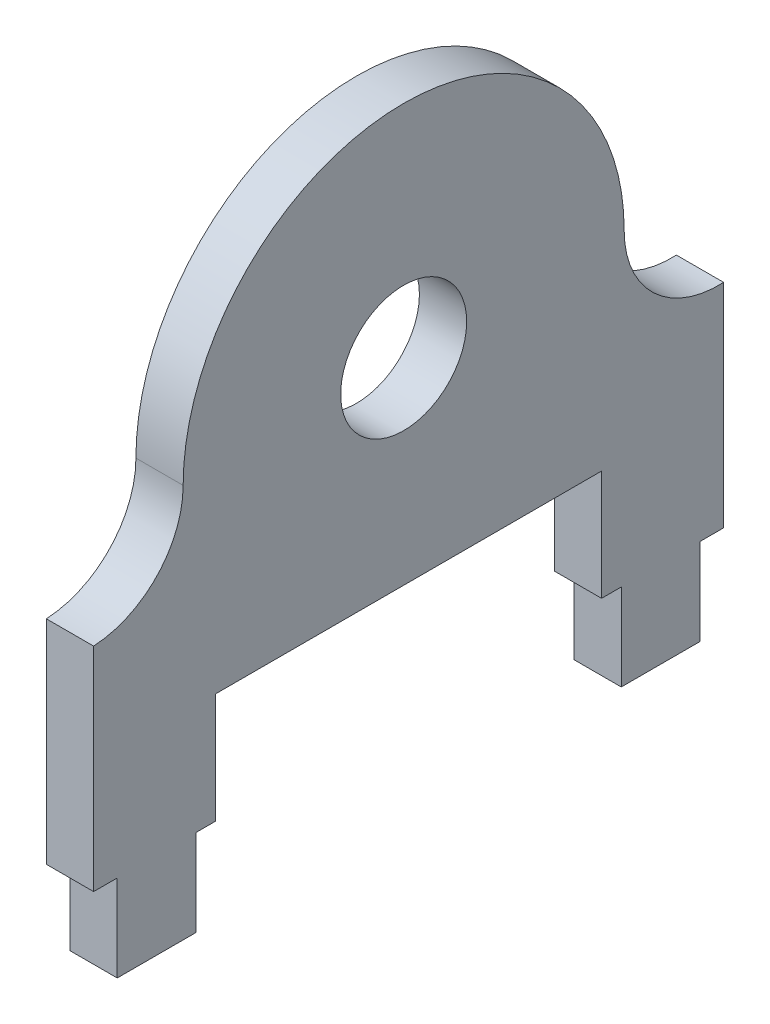
SolidWorks part; units mm, degrees
ref_plane "Front Plane" through (0, 0, 0) normal (0, 0, 1) x (1, 0, 0)
ref_plane "Top Plane" through (0, 0, 0) normal (0, 1, 0) x (1, 0, 0)
ref_plane "Right Plane" through (0, 0, 0) normal (1, 0, 0) x (0, 0, -1)
sketch "Sketch3" plane through (0, 0, 0) normal (1, 0, 0) x (0, 0, -1)
  line L0 (-16.8284, -0.1679) -> (-16.8284, -13.6679)
  line L1 (-16.8284, -13.6679) -> (-15.3284, -13.6679)
  line L2 (-15.3284, -13.6679) -> (-15.3284, -19.1679)
  line L3 (-15.3284, -19.1679) -> (-10.3284, -19.1679)
  line L4 (-10.3284, -19.1679) -> (-10.3284, -13.6679)
  line L5 (-10.3284, -13.6679) -> (-9.0784, -13.6679)
  line L6 (-9.0784, -13.6679) -> (-9.0784, -6.6679)
  line L7 (-9.0784, -6.6679) -> (15.4216, -6.6679)
  line L8 (15.4216, -6.6679) -> (15.4216, -13.6679)
  line L9 (15.4216, -13.6679) -> (16.6716, -13.6679)
  line L10 (16.6716, -13.6679) -> (16.6716, -19.1679)
  line L11 (16.6716, -19.1679) -> (21.6716, -19.1679)
  line L12 (21.6716, -19.1679) -> (21.6716, -13.6679)
  line L13 (21.6716, -13.6679) -> (23.1716, -13.6679)
  line L14 (23.1716, -13.6679) -> (23.1716, -0.1679)
  circle A0 centre (2.8568, 5.8321) radius 4
  arc A1 (16.8568, 5.8321) -> (-11.1432, 5.8263) centre (2.8568, 5.8321) ccw
  arc A2 (23.1716, -0.1679) -> (16.8568, 5.8321) centre (22.8646, 5.8321) cw
  arc A3 (-16.8284, -0.1679) -> (-11.1432, 5.8263) centre (-17.1432, 5.8238) ccw
  circle A4 centre (2.8568, 5.8321) radius 14 construction
  dimension "D1" = 5.5
  dimension "D9" = 28
  dimension "D10" = 8
  dimension "D11" = 7
  dimension "D2" = 40
  dimension "D3" = 5
  dimension "D4" = 1.25
  dimension "D5" = 13.5
  dimension "D6" = 1.5
  dimension "D7" = 1.25
  dimension "D8" = 25
extrude "Boss-Extrude1" add sketch "Sketch3" along normal blind 3
